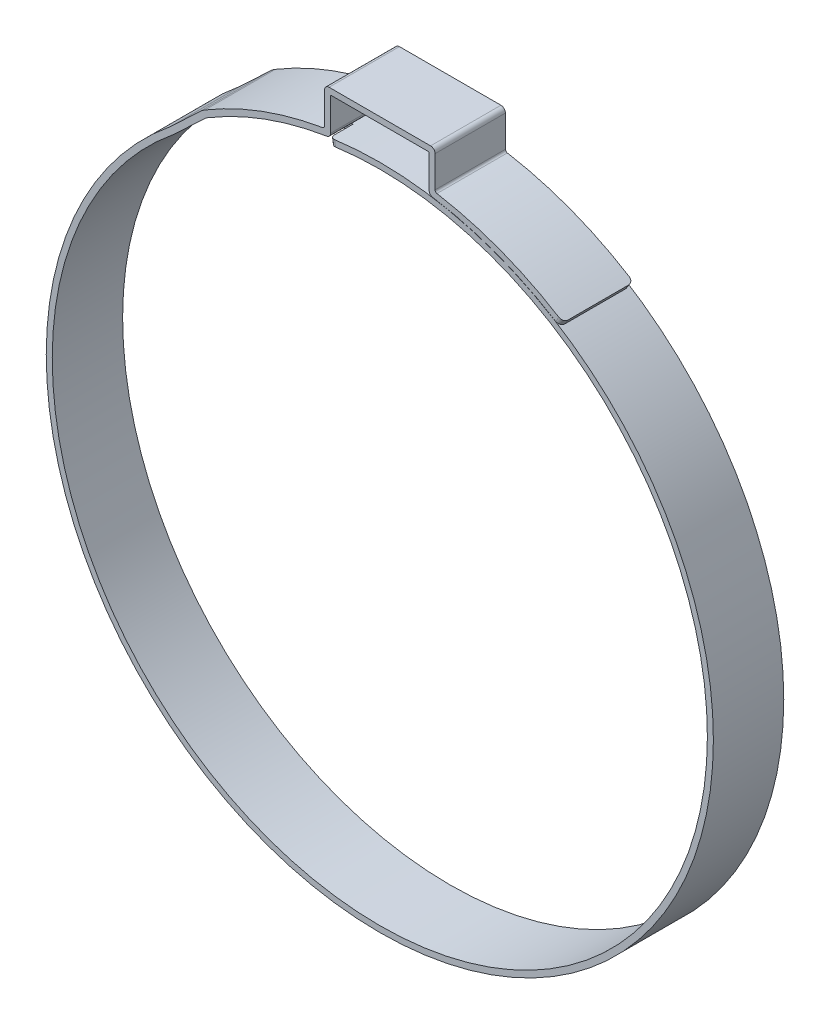
SolidWorks part; units mm, degrees
material "Alloy Steel"
ref_plane "Front" through (0, 0, 0) normal (0, 0, 1) x (1, 0, 0)
ref_plane "Top" through (0, 0, 0) normal (0, 1, 0) x (1, 0, 0)
ref_plane "Right" through (0, 0, 0) normal (1, 0, 0) x (0, 0, -1)
sketch "Sketch1" plane through (0, 0, 0) normal (0, 0, 1) x (1, 0, 0)
  line L0 (0, 0) -> (0, 33.25) construction
  line L1 (0, 33.25) -> (0, 37.2641) construction
  line L2 (-5, 33.25) -> (5, 33.25) construction
  line L3 (-5, 33.5141) -> (-5, 37.2641) construction
  line L4 (-5, 37.2641) -> (5, 37.2641) construction
  line L5 (5, 37.2641) -> (5, 33.5141) construction
  line L6 (-33.25, 0) -> (0, 0) construction
  line L7 (0, 0) -> (33.25, 0) construction
  line L8 (-5.6096, 33.5141) -> (-5.6096, 37.8737)
  line L9 (-5, 33.5141) -> (-5.6096, 33.5141)
  line L10 (-5.6096, 37.8737) -> (5.6096, 37.8737)
  line L11 (5.6096, 37.8737) -> (5.6096, 33.5141)
  line L12 (5.6096, 33.5141) -> (5, 33.5141)
  line L13 (0, 37.2641) -> (0, 37.8737) construction
  line L14 (-5, 33.5141) -> (5, 33.5141)
  circle A0 centre (0, 0) radius 33.25 construction
  circle A1 centre (0, 0) radius 33.8596 construction
  circle A2 centre (0, 0) radius 33.885 construction
  dimension "D3" = 3.75
  dimension "D1" = 0.6096
extrude "Boss-Extrude1" add sketch "Sketch1" along normal mid plane 7.1437
sketch "Sketch4" plane through (0, 37.8737, 0) normal (0, 1, 0) x (1, 0, 0)
  line L0 (-1.9284, 0) -> (-3, 0) construction
  line L1 (0, -1.0716) -> (0, 1.0716) construction
  line L2 (-1.9284, 0) -> (1.9284, 0) construction
  line L3 (-33.25, 0) -> (33.25, 0) construction
  line L4 (-1.9284, 1.0716) -> (1.9284, 1.0716)
  line L5 (-1.9284, -1.0716) -> (1.9284, -1.0716)
  line L6 (1.9284, 0) -> (3, 0) construction
  arc A0 (-1.9284, 1.0716) -> (-1.9284, -1.0716) centre (-1.9284, 0) ccw
  arc A1 (1.9284, -1.0716) -> (1.9284, 1.0716) centre (1.9284, 0) ccw
  point P5 (0, 0)
  dimension "D2" = 2.1431
  dimension "D1" = 6
extrude "Cut-Extrude1" [suppressed] cut sketch "Sketch4" against normal blind 0.75
fillet "Fillet1" [suppressed] radius 0.4875
fillet "Fillet2" [suppressed] radius 0.1875
shell "Shell1" thickness 0.6096
sketch "Sketch5" plane through (0, 0, 0) normal (0, 0, 1) x (1, 0, 0)
  line L0 (18.2782, 28.5325) -> (0, 0) construction
  line L1 (5, 33.5141) -> (0, 0) construction
  arc A0 (5, 33.5141) -> (18.2782, 28.5325) centre (0, 0) cw
  dimension "Connector Strap Length" = 14.2875
extrude "Extrude-Thin3" add sketch "Sketch5" along normal mid plane 7.1437 thin thin type one direction reverse wall 0.6096
sketch "Sketch6" plane through (0, 0, 0) normal (0, 0, 1) x (1, 0, 0)
  line L0 (-17.659, 28.9197) -> (0, 0) construction
  line L2 (-17.8395, 28.7493) -> (-20.8191, 25.9344)
  line L3 (-26.8688, 19.5865) -> (0, 0) construction
  line L4 (-20.8839, 25.8732) -> (0, 0) construction
  arc A0 (-5, 33.5141) -> (-17.439, 29.053) centre (0, 0) ccw
  arc A1 (-26.8688, 19.5865) -> (-5, 32.8719) centre (0, 0) ccw
  arc A2 (-20.8191, 25.9344) -> (-20.9509, 25.819) centre (-22.4175, 27.6264) cw
  arc A3 (-17.439, 29.053) -> (-17.8395, 28.7493) centre (-16.2412, 27.0574) ccw
  arc A4 (-26.8688, 19.5865) -> (-20.9509, 25.819) centre (0, 0) cw
  circle A5 centre (0, 0) radius 33.25 construction
  dimension "D4" = 2.3275
  dimension "D2" = 15
  dimension "D3" = 7.5
  dimension "D1" = 13.3
extrude "Extrude-Thin4" add sketch "Sketch6" along normal mid plane 7.1437 thin
sketch "Sketch7" plane through (0, 0, 0) normal (0, 0, 1) x (1, 0, 0)
  line L1 (-17.7527, 29.5756) -> (-17.439, 29.053)
  line L3 (-17.439, 29.053) -> (0, 0)
  line L4 (-32.8501, 8.2061) -> (-35.2405, 8.8033)
  line L5 (-17.7527, 29.5756) -> (-18.6939, 31.1436)
  line L6 (0, 0) -> (-32.8501, 8.2061)
  arc A0 (-35.2405, 8.8033) -> (-18.6939, 31.1436) centre (0, 0) cw
  arc A1 (-17.439, 29.053) -> (-17.8395, 28.7493) centre (-16.2412, 27.0574) ccw construction
  arc A2 (-5, 33.5141) -> (-17.439, 29.053) centre (0, 0) ccw construction
  arc A10 (-21.335, 26.2924) -> (-5.0917, 33.4746) centre (0, 0) ccw construction
  dimension "D1" = 1.8288
  dimension "D2" = 45
extrude "Cut-Extrude2" [suppressed] cut sketch "Sketch7" against normal mid plane 2.432
sketch "Sketch8" [suppressed] plane through (0, 0, 0) normal (0, 0, 1) x (1, 0, 0)
  line L0 (-29.1891, 21.6191) -> (0, 0) construction
  line L1 (0, 0) -> (-32.2587, 8.0584) construction
  line L2 (0, 0) -> (-17.439, 29.053) construction
  line L3 (-27.2092, 20.1527) -> (-26.7194, 19.7899) construction
  line L4 (-22.7122, 24.9952) -> (0, 0) construction
  line L5 (-30.1645, 14.2199) -> (0, 0) construction
  arc A0 (-5, 33.5141) -> (-17.439, 29.053) centre (0, 0) ccw construction
  arc A1 (-5, 33.5141) -> (-17.439, 29.053) centre (0, 0) ccw construction
  arc A2 (-18.6939, 31.1436) -> (-35.2405, 8.8033) centre (0, 0) ccw construction
  arc A3 (-32.2587, 8.0584) -> (-5, 32.8719) centre (0, 0) ccw construction
  circle A4 centre (0, 0) radius 33.8596 construction
  arc A5 (-20.9509, 25.819) -> (-5, 32.8719) centre (0, 0) ccw construction
  circle A6 centre (0, 0) radius 33.25 construction
  arc A7 (-32.2587, 8.0584) -> (-30.1645, 14.2199) centre (5.8944, -1.4725) cw
  arc A8 (-30.1645, 14.2199) -> (-22.7122, 24.9952) centre (0.8964, 0.7026) cw
  arc A9 (-22.7122, 24.9952) -> (-17.439, 29.053) centre (-2.551, 4.2499) cw
  point P19 (-26.9643, 19.9713)
  dimension "D1" = 22.5
extrude "Extrude-Thin5" [suppressed] add sketch "Sketch8" along normal mid plane 2.3813 thin
sketch "Sketch12" [suppressed] plane through (0, 0, 0) normal (0, 0, 1) x (1, 0, 0)
  line L0 (-5.6453, -0.2315) -> (0, 0) construction
  line L1 (0, 0) -> (-4.5478, 4.1895) construction
  line L2 (-5.5488, 2.0363) -> (0, 0) construction
  arc A0 (-2.75, 5.5382) -> (-4.5478, 4.1895) centre (0, 0) ccw construction
  arc A1 (-2.75, 5.5382) -> (-4.5478, 4.1895) centre (0, 0) ccw construction
  arc A2 (-5.6453, -0.2315) -> (0, -5.65) centre (0, 0) ccw construction
  arc A3 (-5.6453, -0.2315) -> (-5.5488, 2.0363) centre (7.9561, 0.3262) cw
  arc A4 (-5.5488, 2.0363) -> (-4.5478, 4.1895) centre (-1.6784, 1.5462) cw
  dimension "D1" = 22.5
extrude "Extrude-Thin7" [suppressed] add sketch "Sketch12" along normal mid plane 2.3813 thin
sketch "Sketch9" plane through (0, 0, 0) normal (0, 0, 1) x (1, 0, 0)
  line L0 (0, 0) -> (-17.1122, 28.5085) construction
  line L4 (-17.7527, 29.5756) -> (-17.1122, 28.5085) construction
  arc A0 (-5, 32.8719) -> (-17.1122, 28.5085) centre (0, 0) ccw
  circle A1 centre (0, 0) radius 33.25 construction
extrude "Extrude-Thin6" add sketch "Sketch9" along normal mid plane 2.3813 thin
sketch "Sketch10" plane through (0, 0, 0) normal (0, 0, 1) x (1, 0, 0)
  line L0 (0, 0) -> (16.4197, 30.3359) construction
  line L1 (0, 0) -> (15.292, 30.9198) construction
  line L2 (0, 0) -> (14.1435, 31.4617) construction
  line L3 (0, 0) -> (12.9758, 31.961) construction
  line L4 (0, 0) -> (18.607, 29.0458) construction
  line L5 (0, 0) -> (11.7906, 32.417) construction
  line L6 (0, 0) -> (10.5893, 32.829) construction
  line L7 (10.5893, 32.829) -> (10.3944, 32.2247)
  line L8 (11.7906, 32.417) -> (11.5735, 31.8202)
  line L9 (12.9758, 31.961) -> (12.7369, 31.3726)
  line L10 (14.1435, 31.4617) -> (13.8831, 30.8825)
  line L11 (15.292, 30.9198) -> (15.0105, 30.3506)
  line L12 (16.4197, 30.3359) -> (16.1175, 29.7775)
  arc A0 (18.607, 29.0458) -> (5.6096, 34.0354) centre (0, 0) ccw construction
  arc A1 (10.5893, 32.829) -> (11.7906, 32.417) centre (0, 0) cw
  circle A2 centre (0, 0) radius 33.8596 construction
  arc A3 (10.3944, 32.2247) -> (11.5735, 31.8202) centre (0, 0) cw
  arc A4 (12.9758, 31.961) -> (14.1435, 31.4617) centre (0, 0) cw
  arc A5 (15.292, 30.9198) -> (16.4197, 30.3359) centre (0, 0) cw
  arc A6 (12.7369, 31.3726) -> (13.8831, 30.8825) centre (0, 0) cw
  arc A7 (15.0105, 30.3506) -> (16.1175, 29.7775) centre (0, 0) cw
  dimension "D3" = 1.27
  dimension "D4" = 1.27
  dimension "D5" = 1.27
  dimension "D6" = 1.27
extrude "Cut-Extrude3" [suppressed] cut sketch "Sketch10" against normal mid plane 1.7859
fillet "Fillet4" radius 0.4572 4 edges at (5.6096, 37.8737, 0) (-5.6096, 37.8737, 0) (5, 33.5141, 0) (-5, 33.5141, 0)
fillet "Fillet5" radius 0.2286 2 edges at (5.6096, 34.0354, 0) (-5.6096, 34.0354, 0)
fillet "Fillet6" radius 0.1143 2 edges at (5, 37.2641, 0) (-5, 37.2641, 0)
fillet "Fillet7" radius 0.508 6 edges at (18.4426, 28.7891, -3.5719) (18.4426, 28.7891, 3.5719) (-5.0458, 33.1732, -3.5719) (-5.0458, 33.1732, 3.5719) (-17.2691, 28.7698, 1.1906) (-17.2691, 28.7698, -1.1906)
sketch "Sketch11" [suppressed] plane through (0, 0, 0) normal (0, 0, 1) x (1, 0, 0)
  line L0 (15.292, 30.9198) -> (15.0105, 30.3506) construction
  line L2 (15.292, 30.9198) -> (15.0217, 30.3734) construction
  line L3 (16.4197, 30.3359) -> (16.1175, 29.7775) construction
  line L4 (16.1296, 29.7998) -> (16.4197, 30.3359) construction
  line L5 (15.0332, 30.3393) -> (16.0839, 30.8881)
  line L6 (15.0332, 30.3393) -> (15.3147, 30.9085) construction
  line L8 (17.0883, 30.3439) -> (16.9432, 30.0759)
  line L9 (16.9432, 30.0759) -> (0, 0) construction
  line L10 (12.7605, 31.3631) -> (13.4542, 31.7626)
  line L11 (14.2416, 31.6181) -> (13.9063, 30.8721)
  line L12 (11.8769, 32.5801) -> (11.081, 32.6663)
  line L13 (11.8769, 32.5801) -> (11.5974, 31.8115)
  line L14 (11.5822, 31.8441) -> (11.7906, 32.417) construction
  line L15 (13.8935, 30.9057) -> (14.1435, 31.4617) construction
  line L16 (10.4186, 32.2169) -> (10.6135, 32.8212) construction
  line L17 (10.5893, 32.829) -> (10.4022, 32.2488) construction
  line L18 (12.7605, 31.3631) -> (12.9993, 31.9514) construction
  line L19 (12.9758, 31.961) -> (12.7465, 31.3962) construction
  line L20 (11.081, 32.6663) -> (10.4186, 32.2169)
  line L21 (13.4542, 31.7626) -> (14.2416, 31.6181)
  line L22 (16.4095, 30.3704) -> (16.0951, 29.7896) construction
  line L23 (16.4095, 30.3704) -> (15.6999, 29.9998)
  arc A0 (16.4095, 30.3704) -> (16.9432, 30.0759) centre (0, 0) cw
  arc A1 (-21.335, 26.2924) -> (-4.5889, 33.5472) centre (0, 0) ccw construction
  arc A2 (16.0839, 30.8881) -> (17.0883, 30.3439) centre (0, 0) cw
  arc A3 (15.0332, 30.3393) -> (15.6999, 29.9998) centre (0, 0) cw
  arc A5 (18.1772, 29.3166) -> (5.7998, 34.0035) centre (0, 0) ccw construction
  arc A6 (12.7605, 31.3631) -> (13.9063, 30.8721) centre (0, 0) cw
  arc A7 (10.4186, 32.2169) -> (11.5974, 31.8115) centre (0, 0) cw
  point P24 (11.8144, 32.4083)
  point P41 (14.1666, 31.4513)
  dimension "D2" = 0.0254
  dimension "D5" = 0.6096
  dimension "D7" = 0.0254
  dimension "D8" = 0.0254
  dimension "D9" = 0.0254
  dimension "D10" = 0.0254
  dimension "D11" = 0.1829
  dimension "D12" = 0.1829
  dimension "D3" = 0.0254
  dimension "D6" = 0.6096
  dimension "D13" = 0.3048
extrude "Boss-Extrude2" [suppressed] add sketch "Sketch11" along normal mid plane 1.6589
sketch "Ref" plane through (0, 0, 0) normal (0, 0, 1) x (1, 0, 0)
  line L1 (5.1524, 37.8737) -> (-5.1524, 37.8737) construction
  line L2 (5.6096, 37.8737) -> (-5.6096, 37.8737)
  line L4 (4.8857, 37.2641) -> (-4.8857, 37.2641) construction
  line L7 (5.6096, 37.2641) -> (-5.6096, 37.2641)
  line L8 (-5.6096, 37.4165) -> (-5.6096, 34.2289) construction
  line L9 (5.6096, 34.2289) -> (5.6096, 37.4165) construction
equation "\"D3@Sketch1\" = \"Ear Width (Inside)@Sketch1\" * .375"
equation "\"D2@Sketch4\" = \"Band Wd@Boss-Extrude1\" * .3"
equation "\"D1@Sketch4\" = \"Ear Width (Inside)@Sketch1\" * .6"
equation "\"D1@Cut-Extrude1\" = \"D3@Sketch1\" * .2"
equation "\"D1@Shell1\" = \"Band Thickness@Sketch1\""
equation "\"D5@Extrude-Thin3\" = \"Band Thickness@Sketch1\""
equation "\"D1@Extrude-Thin3\" = \"Band Wd@Boss-Extrude1\""
equation "\"D5@Extrude-Thin4\" = \"Band Thickness@Sketch1\""
equation "\"D1@Extrude-Thin4\" = \"Band Wd@Boss-Extrude1\""
equation "\"D1@Fillet4\" = \"Band Thickness@Sketch1\" * .75"
equation "\"D1@Fillet5\" = \"D1@Fillet4\" * .5"
equation "\"D1@Fillet6\" = \"D1@Fillet4\" * .25"
equation "\"D1@Fillet1\" = \"D1@Cut-Extrude1\" * .65"
equation "\"D1@Fillet2\" = \"D1@Cut-Extrude1\" * .25"
equation "\"D1@Sketch1\" = \"Band Thickness@Sketch1\""
equation "\"D1@Cut-Extrude2\" = ( \"Band Wd@Boss-Extrude1\" / 3 ) + .002"
equation "\"D1@Extrude-Thin5\" = \"Band Wd@Boss-Extrude1\" / 3"
equation "\"D5@Extrude-Thin5\" = \"Band Thickness@Sketch1\""
equation "\"D1@Extrude-Thin6\" = \"D1@Extrude-Thin5\""
equation "\"D5@Extrude-Thin6\" = \"Band Thickness@Sketch1\""
equation "\"D1@Cut-Extrude3\" = \"Band Wd@Boss-Extrude1\" * .25"
equation "\"D11@Sketch11\" = \"Band Thickness@Sketch1\" * .3"
equation "\"D12@Sketch11\" = \"D11@Sketch11\""
equation "\"D1@Boss-Extrude2\" = \"D1@Cut-Extrude3\" - .005"
equation "\"D4@Sketch6\" = \"Clamp ID@Sketch1\" * .035"
equation "\"D1@Sketch7\" = \"Band Thickness@Sketch1\" * 3"
equation "\"D3@Sketch10\" = \"D2@Sketch10\""
equation "\"D4@Sketch10\" = \"D3@Sketch10\""
equation "\"D5@Sketch10\" = \"D2@Sketch10\""
equation "\"D6@Sketch10\" = \"D2@Sketch10\""
equation "\"D5@Sketch11\" = \"Band Thickness@Sketch1\""
equation "\"D6@Sketch11\" = \"Band Thickness@Sketch1\""
equation "\"D13@Sketch11\" = \"Band Thickness@Sketch1\" / 2"
equation "\"D1@Sketch6\" = \"Clamp ID@Sketch1\" * .2"
equation "\"D1@Extrude-Thin7\" = \"Band Wd@Boss-Extrude1\" / 3"
equation "\"D5@Extrude-Thin7\" = \"Band Thickness@Sketch1\""
